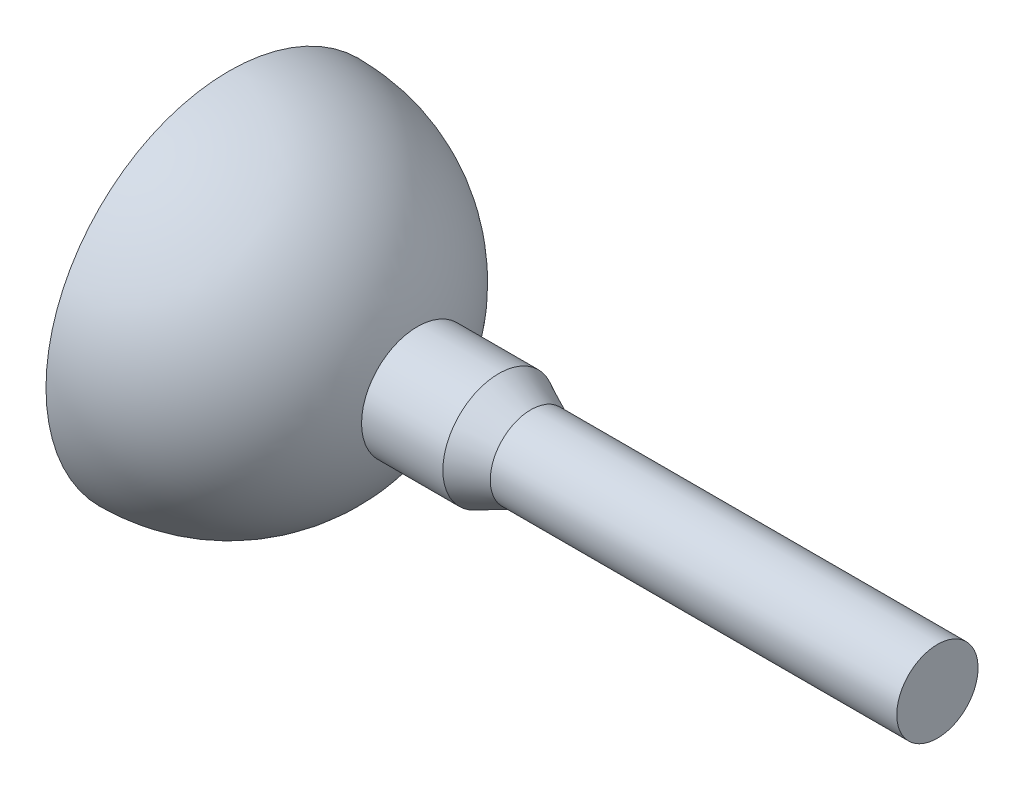
SolidWorks part; units mm, degrees
ref_plane "前视基准面" through (0, 0, 0) normal (0, 0, 1) x (1, 0, 0)
ref_plane "上视基准面" through (0, 0, 0) normal (0, 1, 0) x (1, 0, 0)
ref_plane "右视基准面" through (0, 0, 0) normal (1, 0, 0) x (0, 0, -1)
sketch "草图1" plane through (0, 0, 0) normal (0, 0, 1) x (1, 0, 0)
  line L0 (0, 0) -> (80.9867, 0) construction
  line L1 (-1.169, 2) -> (-1.169, 2.75)
  line L2 (-1.169, 2.75) -> (2.831, 2.75)
  line L3 (24.4121, 0) -> (-10.444, 0)
  line L4 (4.4121, 2) -> (24.4121, 2)
  line L5 (2.831, 2.75) -> (4.4121, 2)
  line L6 (24.4121, 2) -> (24.4121, 0)
  line L7 (0, 0) -> (-6.9483, 0) construction
  line L8 (-18.444, 7.5066) -> (-18.444, -12.7893) construction
  line L9 (-1.169, 2) -> (-1.669, 2)
  line L10 (-10.444, 0) -> (-10.444, 9)
  arc A0 (-1.669, 2) -> (-10.444, 9) centre (-10.444, 0) ccw
  dimension "D4" = 18
  dimension "D5" = 8
  dimension "D1" = 4
  dimension "D2" = 5.5
  dimension "D3" = 4
  dimension "D6" = 20
  dimension "D7" = 0.5
revolve "旋转1" add sketch "草图1" angle 360 about L0
